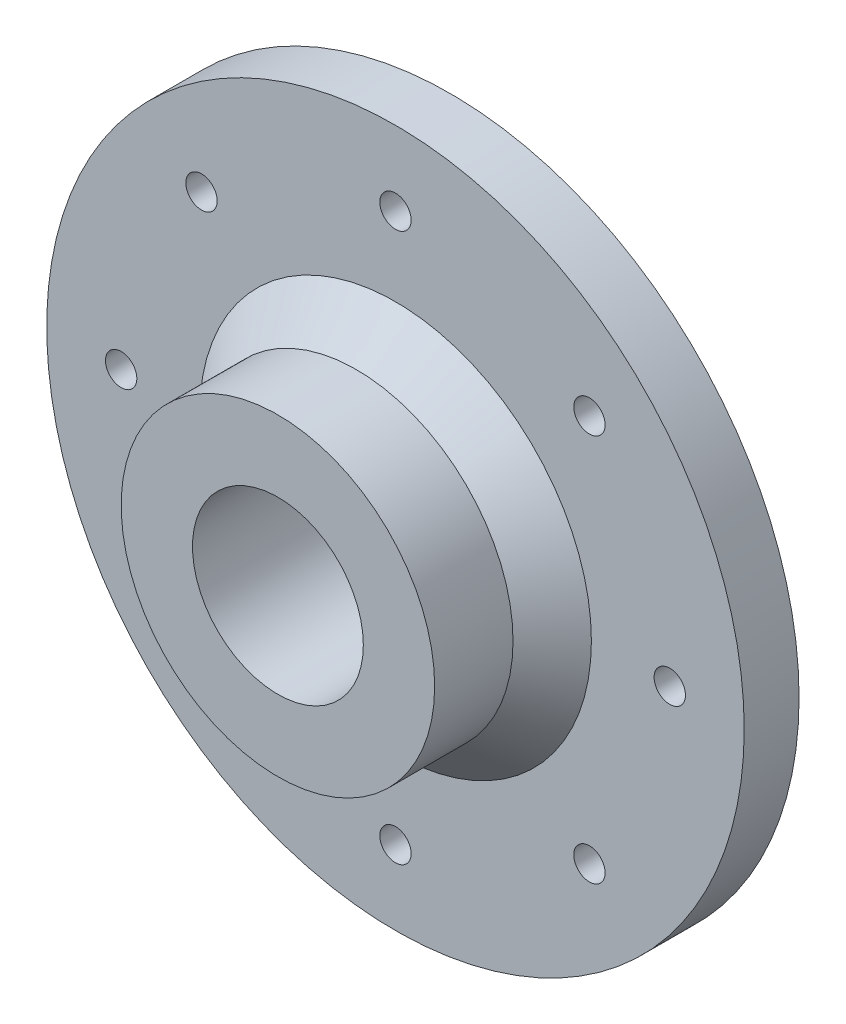
SolidWorks part; units mm, degrees
ref_plane "Спереди" through (0, 0, 0) normal (0, 0, 1) x (1, 0, 0)
ref_plane "Сверху" through (0, 0, 0) normal (0, 1, 0) x (1, 0, 0)
ref_plane "Справа" through (0, 0, 0) normal (1, 0, 0) x (0, 0, -1)
sketch "Эскиз1" plane through (0, 0, 0) normal (0, 0, 1) x (1, 0, 0)
  circle A0 centre (0, 0) radius 10.9
  circle A1 centre (0, 0) radius 44.5
extrude "Вытянуть1" add sketch "Эскиз1" along normal blind 7
sketch "Эскиз2" plane through (0, 0, 7) normal (0, 0, 1) x (1, 0, 0)
  circle A0 centre (0, 0) radius 10.9
  circle A1 centre (0, 0) radius 20
extrude "Вытянуть2" add sketch "Эскиз2" along normal blind 15
sketch "Эскиз3" plane through (0, 0, 7) normal (0, 0, 1) x (1, 0, 0)
  circle A0 centre (0, 35) radius 2
  circle A1 centre (24.7487, 24.7487) radius 2
  circle A2 centre (35, 0) radius 2
  circle A3 centre (24.7487, -24.7487) radius 2
  circle A4 centre (0, -35) radius 2
  circle A5 centre (-24.7487, -24.7487) radius 2
  circle A6 centre (-35, 0) radius 2
  circle A7 centre (-24.7487, 24.7487) radius 2
  dimension "D1" = 35
extrude "Вытянуть3" cut sketch "Эскиз3" against normal through all
chamfer "Фаска1" distance 5 angle 45 1 edges at (20, 0, 7)
